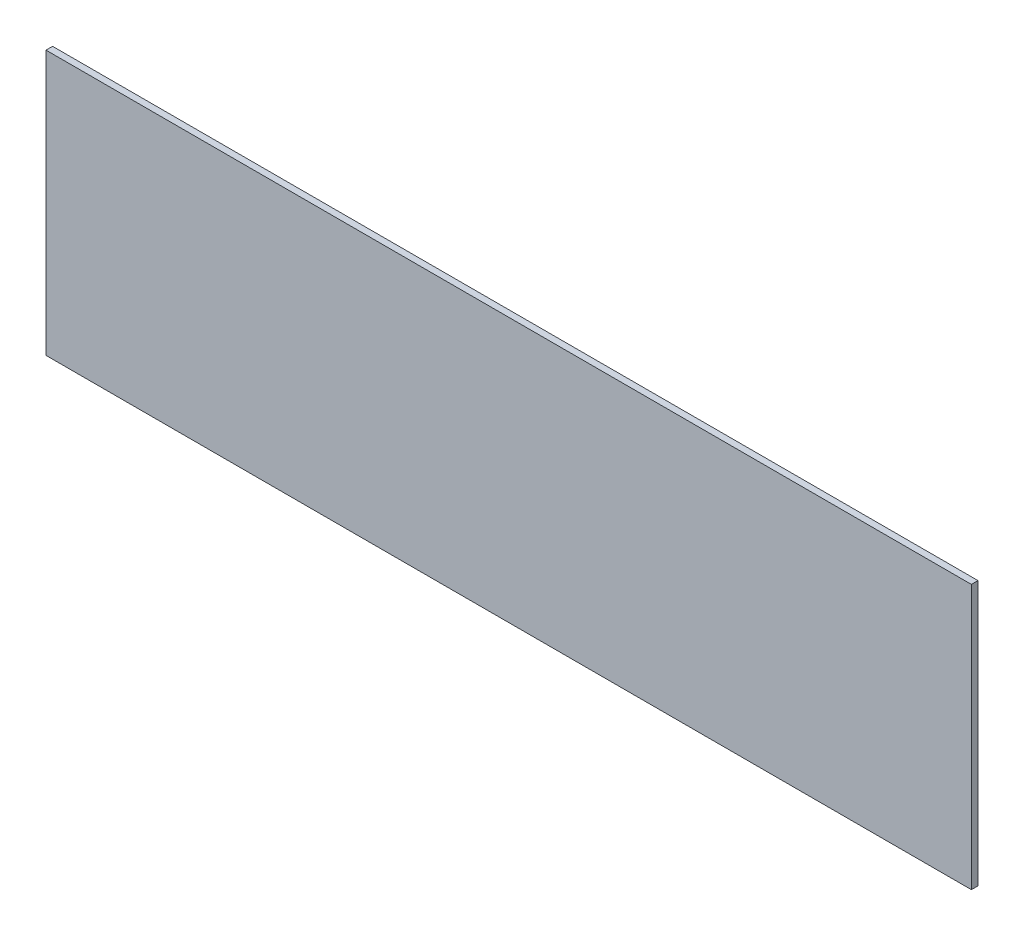
SolidWorks part; units mm, degrees
ref_plane "Front Plane" through (0, 0, 0) normal (0, 0, 1) x (1, 0, 0)
ref_plane "Top Plane" through (0, 0, 0) normal (0, 1, 0) x (1, 0, 0)
ref_plane "Right Plane" through (0, 0, 0) normal (1, 0, 0) x (0, 0, -1)
sketch "Sketch1" plane through (0, 0, 0) normal (0, 0, 1) x (1, 0, 0)
  line L1 (-700, 100) -> (700, 100)
  line L2 (-700, 100) -> (-700, -300)
  line L3 (-700, -300) -> (700, -300)
  line L4 (700, 100) -> (700, -300)
  point P0 (0, 0)
  dimension "D1" = 1400
  dimension "D2" = 400
extrude "Boss-Extrude1" add sketch "Sketch1" along normal blind 10
